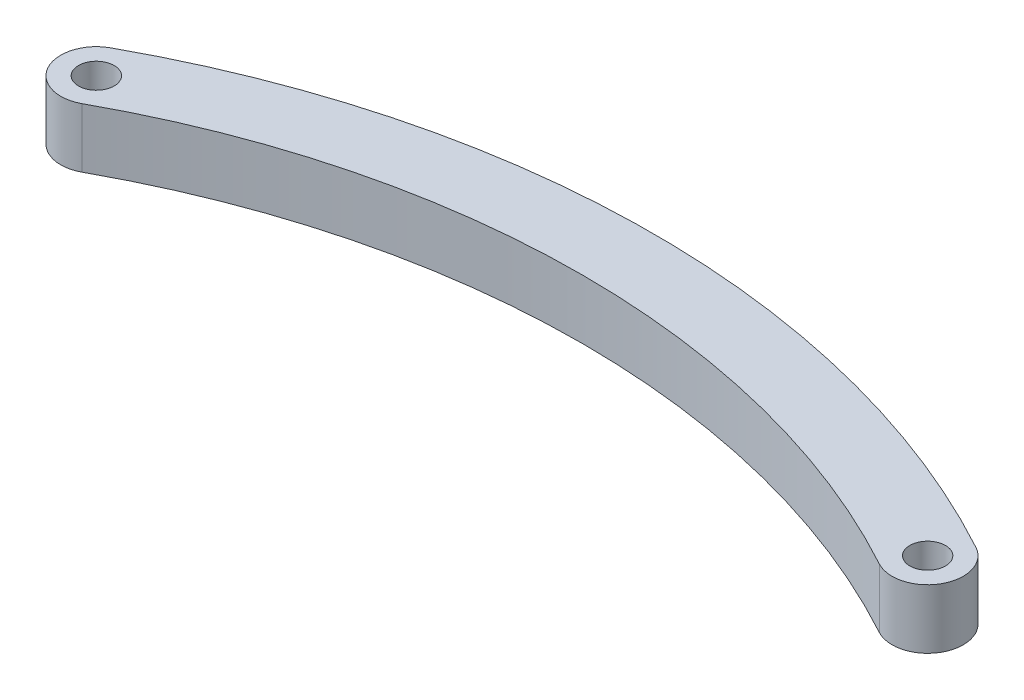
SolidWorks part; units mm, degrees
ref_plane "Front Plane" through (0, 0, 0) normal (0, 0, 1) x (1, 0, 0)
ref_plane "Top Plane" through (0, 0, 0) normal (0, 1, 0) x (1, 0, 0)
ref_plane "Right Plane" through (0, 0, 0) normal (1, 0, 0) x (0, 0, -1)
sketch "Esquisse1" plane through (0, 0, 0) normal (0, 1, 0) x (1, 0, 0)
  line L0 (-35, 0) -> (0, 0) construction
  line L1 (0, 0) -> (35, 0) construction
  circle A0 centre (-35, 0) radius 1.5
  circle A1 centre (35, 0) radius 1.5
  circle A2 centre (-35, 0) radius 3
  circle A3 centre (35, 0) radius 3
  circle A4 centre (0, -64.0625) radius 70
  circle A5 centre (0, -64.0625) radius 76
  dimension "D2" = 3
  dimension "D3" = 6
  dimension "D4" = 140
  dimension "D5" = 152
  dimension "D1" = 35
extrude "Boss.-Extru.1" add sketch "Esquisse1" along normal blind 5 contours A3 A5 A2 A4 | A2 A0 | A3 A1
